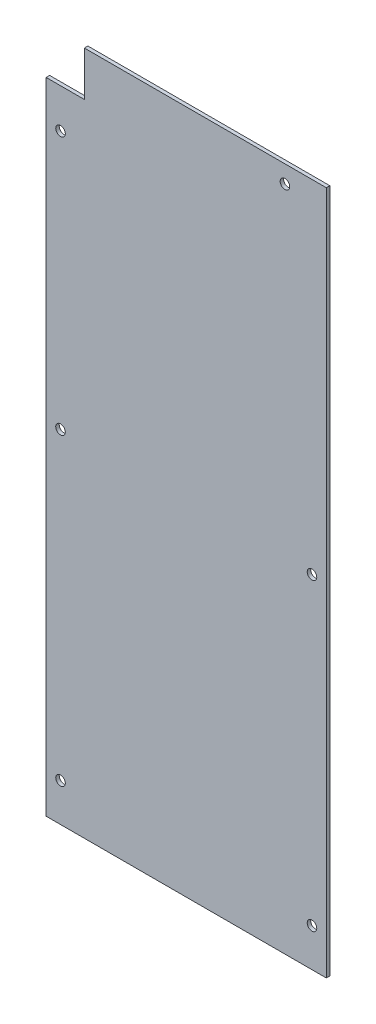
SolidWorks part; units mm, degrees
material "FR4"
ref_plane "Front Plane" through (0, 0, 0) normal (0, 0, 1) x (1, 0, 0)
ref_plane "Top Plane" through (0, 0, 0) normal (0, 1, 0) x (1, 0, 0)
ref_plane "Right Plane" through (0, 0, 0) normal (1, 0, 0) x (0, 0, -1)
sketch "Sketch3" plane through (0, 0, 0) normal (0, 0, 1) x (1, 0, 0)
  line L1 (-43.4055, 36.5752) -> (44.5945, 36.5752)
  line L2 (-43.4055, 36.5752) -> (-43.4055, -178.4248)
  line L3 (-43.4055, -178.4248) -> (44.5945, -178.4248)
  line L4 (44.5945, 36.5752) -> (44.5945, -178.4248)
  dimension "D1" = 215
  dimension "D2" = 88
sketch3d "3DSketch2"
  line L0 (-43.4055, 36.5752, 0) -> (-43.4055, -178.4248, 0) construction
  line L3 (-43.4055, 36.5752, 0) -> (44.5945, 36.5752, 0) construction
  line L4 (44.5945, 36.5752, 0) -> (44.5945, -178.4248, 0) construction
  line L6 (-43.4055, 36.5752, 0) -> (-31.4055, 36.5752, 0)
  line L7 (-43.4055, 36.5752, 0) -> (-43.4055, 22.5761, 0)
  line L8 (-43.4055, 22.5761, 0) -> (-31.4055, 22.5761, 0)
  line L9 (-31.4055, 36.5752, 0) -> (-31.4055, 22.5761, 0)
  circle A0 centre (-38.9055, 10.2552, 0) radius 1.5
  circle A1 centre (-38.9055, -70.9248, 0) radius 1.5
  circle A2 centre (-38.9055, -166.4248, 0) radius 1.5
  circle A3 centre (31.5945, 31.0752, 0) radius 1.5
  circle A4 centre (40.0945, -70.9248, 0) radius 1.5
  circle A5 centre (40.0945, -166.4248, 0) radius 1.5
  point P8 (-38.9055, 10.2552, 1.5)
  point P16 (-38.9055, -70.9248, 1.5)
  point P19 (-38.9055, -166.4248, 1.5)
  point P22 (31.5945, 31.0752, 1.5)
  point P25 (40.0945, -70.9248, 1.5)
  point P28 (40.0945, -166.4248, 1.5)
  dimension "D4" = 4.5
  dimension "D6" = 4.5
  dimension "D8" = 4.5
  dimension "D1" = 44
  dimension "D2" = 13.9991
  dimension "D3" = 12
  dimension "D5" = 26.32
  dimension "D7" = 107.5
  dimension "D9" = 203
  dimension "D10" = 4.5
  dimension "D11" = 12.3209
  dimension "D12" = 13
extrude "Boss-Extrude3" add sketch "Sketch3" along normal blind 1.1
extrude "Cut-Extrude1" cut sketch "3DSketch2" along direction (0, 0, 1) on the side against the normal blind 10
